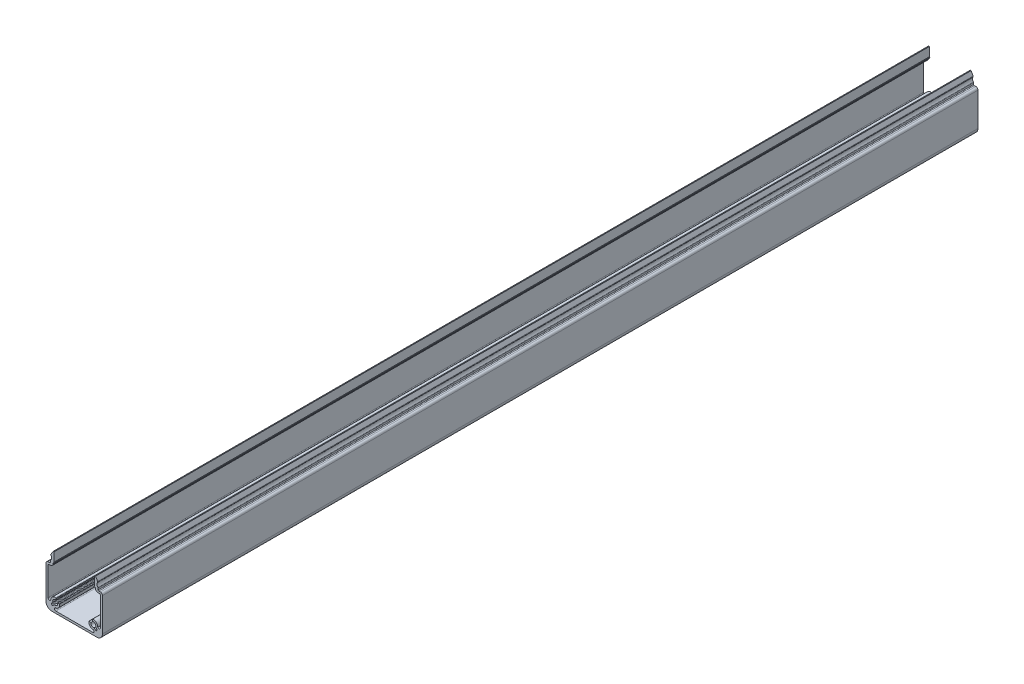
SolidWorks part; units mm, degrees
ref_plane "Front Plane" through (0, 0, 0) normal (0, 0, 1) x (1, 0, 0)
ref_plane "Top Plane" through (0, 0, 0) normal (0, 1, 0) x (1, 0, 0)
ref_plane "Right Plane" through (0, 0, 0) normal (1, 0, 0) x (0, 0, -1)
ref_plane "Plane1" through (0, 0, 20) normal (0, 0, 1) x (1, 0, 0)
sketch "Sketch1" plane through (0, 0, 20) normal (0, 0, 1) x (1, 0, 0)
  line L0 (4, 0) -> (36, 0)
  line L1 (40, 4) -> (40, 27.5)
  line L2 (38.5, 29) -> (37.4085, 29)
  line L3 (36.9085, 29.5) -> (36.9085, 30.572)
  line L4 (36.583, 34.4315) -> (35.1, 37)
  line L5 (35.1, 37) -> (34.5, 37)
  line L6 (34.5, 37) -> (34.5, 30.6727)
  line L7 (34.5, 30.6727) -> (34.1585, 30.5611)
  line L8 (34.1585, 30.5611) -> (34.1585, 29.9899)
  line L9 (34.1585, 29.9899) -> (34.9085, 29.9899)
  line L10 (34.9085, 29.9899) -> (34.9085, 29.7)
  line L11 (36.9085, 27.7) -> (38, 27.7)
  line L12 (38.5, 27.2) -> (38.5, 6.9548)
  line L13 (36.7929, 6.2477) -> (36.6482, 6.3924)
  line L14 (32.7665, 9.2376) -> (33.0471, 8.1904)
  line L15 (35.1484, 5.9123) -> (36.1464, 4.9142)
  line L16 (36.1464, 4.2071) -> (35.7929, 3.8536)
  line L17 (35.0858, 3.8536) -> (34.0877, 4.8516)
  line L18 (31.8096, 6.9529) -> (30.7624, 7.2335)
  line L19 (33.6076, 3.3518) -> (33.7523, 3.2071)
  line L20 (33.0452, 1.5) -> (6.9548, 1.5)
  line L21 (6.2477, 3.2071) -> (6.3924, 3.3518)
  line L22 (9.2376, 7.2335) -> (8.1904, 6.9529)
  line L23 (5.9123, 4.8516) -> (4.9142, 3.8536)
  line L24 (4.2071, 3.8536) -> (3.8536, 4.2071)
  line L25 (3.8536, 4.9142) -> (4.8516, 5.9123)
  line L26 (6.9529, 8.1904) -> (7.2335, 9.2376)
  line L27 (3.3518, 6.3924) -> (3.2071, 6.2477)
  line L28 (1.5, 6.9548) -> (1.5, 27.2)
  line L29 (2, 27.7) -> (3.0915, 27.7)
  line L30 (5.0915, 29.7) -> (5.0915, 29.9899)
  line L31 (5.0915, 29.9899) -> (5.8415, 29.9899)
  line L32 (5.8415, 29.9899) -> (5.8415, 30.5611)
  line L33 (5.8415, 30.5611) -> (5.5, 30.6727)
  line L34 (5.5, 30.6727) -> (5.5, 37)
  line L35 (5.5, 37) -> (4.9, 37)
  line L36 (4.9, 37) -> (3.417, 34.4315)
  line L37 (3.0915, 30.572) -> (3.0915, 29.5)
  line L38 (2.5915, 29) -> (1.5, 29)
  line L39 (0, 27.5) -> (0, 4)
  arc A0 (36, 0) -> (40, 4) centre (36, 4) ccw
  arc A1 (40, 27.5) -> (38.5, 29) centre (38.5, 27.5) ccw
  arc A2 (37.4085, 29) -> (36.9085, 29.5) centre (37.4085, 29.5) cw
  arc A3 (36.9085, 30.572) -> (36.7268, 30.9576) centre (36.4085, 30.572) ccw
  arc A4 (36.7268, 30.9576) -> (36.52, 33.8452) centre (38, 32.5) cw
  arc A5 (36.52, 33.8452) -> (36.583, 34.4315) centre (36.1499, 34.1815) ccw
  arc A6 (34.9085, 29.7) -> (36.9085, 27.7) centre (36.9085, 29.7) ccw
  arc A7 (38, 27.7) -> (38.5, 27.2) centre (38, 27.2) cw
  arc A8 (38.5, 6.9548) -> (36.7929, 6.2477) centre (37.5, 6.9548) cw
  arc A9 (36.6482, 6.3924) -> (33.0095, 9.6116) centre (33.5, 6.5) ccw
  arc A10 (33.0095, 9.6116) -> (32.7665, 9.2376) centre (33.0562, 9.3152) ccw
  arc A11 (33.0471, 8.1904) -> (35.1484, 5.9123) centre (33.5, 6.5) cw
  arc A12 (36.1464, 4.9142) -> (36.1464, 4.2071) centre (35.7929, 4.5607) cw
  arc A13 (35.7929, 3.8536) -> (35.0858, 3.8536) centre (35.4393, 4.2071) cw
  arc A14 (34.0877, 4.8516) -> (31.8096, 6.9529) centre (33.5, 6.5) cw
  arc A15 (30.7624, 7.2335) -> (30.3884, 6.9905) centre (30.6848, 6.9438) ccw
  arc A16 (30.3884, 6.9905) -> (33.6076, 3.3518) centre (33.5, 6.5) ccw
  arc A17 (33.7523, 3.2071) -> (33.0452, 1.5) centre (33.0452, 2.5) cw
  arc A18 (6.9548, 1.5) -> (6.2477, 3.2071) centre (6.9548, 2.5) cw
  arc A19 (6.3924, 3.3518) -> (9.6116, 6.9905) centre (6.5, 6.5) ccw
  arc A20 (9.6116, 6.9905) -> (9.2376, 7.2335) centre (9.3152, 6.9438) ccw
  arc A21 (8.1904, 6.9529) -> (5.9123, 4.8516) centre (6.5, 6.5) cw
  arc A22 (4.9142, 3.8536) -> (4.2071, 3.8536) centre (4.5607, 4.2071) cw
  arc A23 (3.8536, 4.2071) -> (3.8536, 4.9142) centre (4.2071, 4.5607) cw
  arc A24 (4.8516, 5.9123) -> (6.9529, 8.1904) centre (6.5, 6.5) cw
  arc A25 (7.2335, 9.2376) -> (6.9905, 9.6116) centre (6.9438, 9.3152) ccw
  arc A26 (6.9905, 9.6116) -> (3.3518, 6.3924) centre (6.5, 6.5) ccw
  arc A27 (3.2071, 6.2477) -> (1.5, 6.9548) centre (2.5, 6.9548) cw
  arc A28 (1.5, 27.2) -> (2, 27.7) centre (2, 27.2) cw
  arc A29 (3.0915, 27.7) -> (5.0915, 29.7) centre (3.0915, 29.7) ccw
  arc A30 (3.417, 34.4315) -> (3.48, 33.8452) centre (3.8501, 34.1815) ccw
  arc A31 (3.48, 33.8452) -> (3.2732, 30.9576) centre (2, 32.5) cw
  arc A32 (3.2732, 30.9576) -> (3.0915, 30.572) centre (3.5915, 30.572) ccw
  arc A33 (3.0915, 29.5) -> (2.5915, 29) centre (2.5915, 29.5) cw
  arc A34 (1.5, 29) -> (0, 27.5) centre (1.5, 27.5) ccw
  arc A35 (0, 4) -> (4, 0) centre (4, 4) ccw
extrude "Boss-Extrude1" add sketch "Sketch1" against normal blind 620
